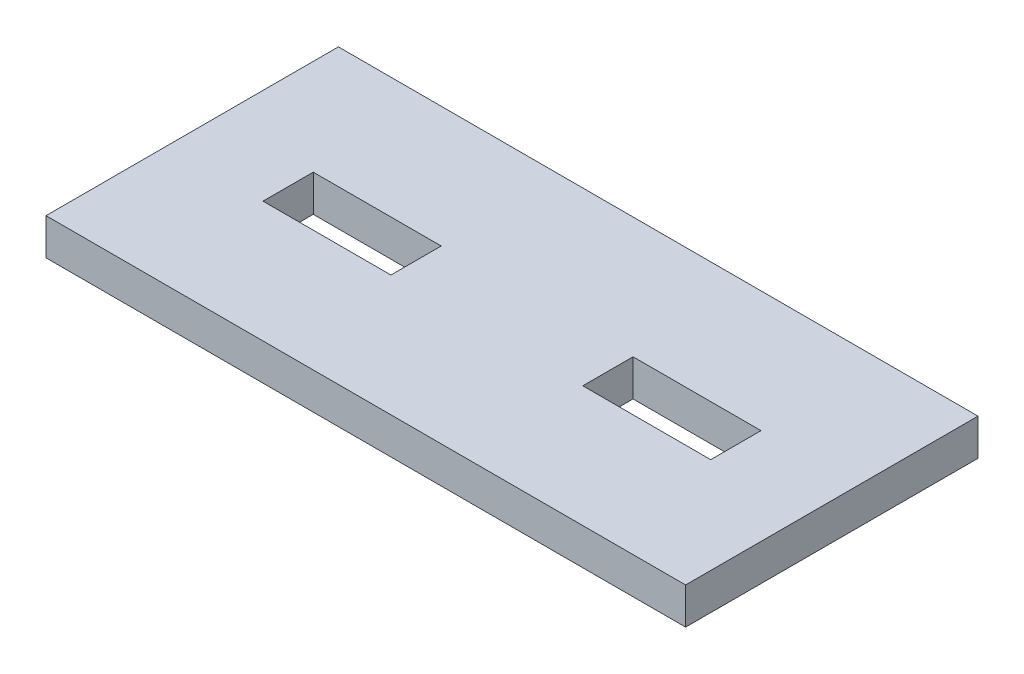
SolidWorks part; units mm, degrees
ref_plane "Front Plane" through (0, 0, 0) normal (0, 0, 1) x (1, 0, 0)
ref_plane "Top Plane" through (0, 0, 0) normal (0, 1, 0) x (1, 0, 0)
ref_plane "Right Plane" through (0, 0, 0) normal (1, 0, 0) x (0, 0, -1)
sketch "Sketch1" plane through (0, 0, 0) normal (0, 1, 0) x (1, 0, 0)
  line L1 (-35, -16) -> (35, -16)
  line L2 (-35, -16) -> (-35, 16)
  line L3 (-35, 16) -> (35, 16)
  line L4 (35, -16) -> (35, 16)
  line L5 (-24.5, -2.75) -> (-10.5, -2.75)
  line L6 (-24.5, -2.75) -> (-24.5, 2.75)
  line L7 (-24.5, 2.75) -> (-10.5, 2.75)
  line L8 (-10.5, -2.75) -> (-10.5, 2.75)
  line L9 (10.5, -2.75) -> (24.5, -2.75)
  line L10 (10.5, -2.75) -> (10.5, 2.75)
  line L11 (10.5, 2.75) -> (24.5, 2.75)
  line L12 (24.5, -2.75) -> (24.5, 2.75)
extrude "Slotted_Bracket_Extrude" add sketch "Sketch1" along normal blind 4
equation "\"ValveDiameter\" = 50mm"
equation "\"MotorGearTeeth\" = 40"
equation "\"OutputGearTeeth\" = 80"
equation "\"GearModule\" = 1.5mm"
equation "\"PressureAngle\" = 20deg"
equation "\"GearCenterDistance\" = 90mm"
equation "\"GearWidth\" = 18mm"
equation "\"OutputShaftDiameter\" = 20mm"
equation "\"BearingOD\" = 47mm"
equation "\"BearingWidth\" = 14mm"
equation "\"PlateThickness\" = 6mm"
equation "\"ValveRotation\" = 90deg"
